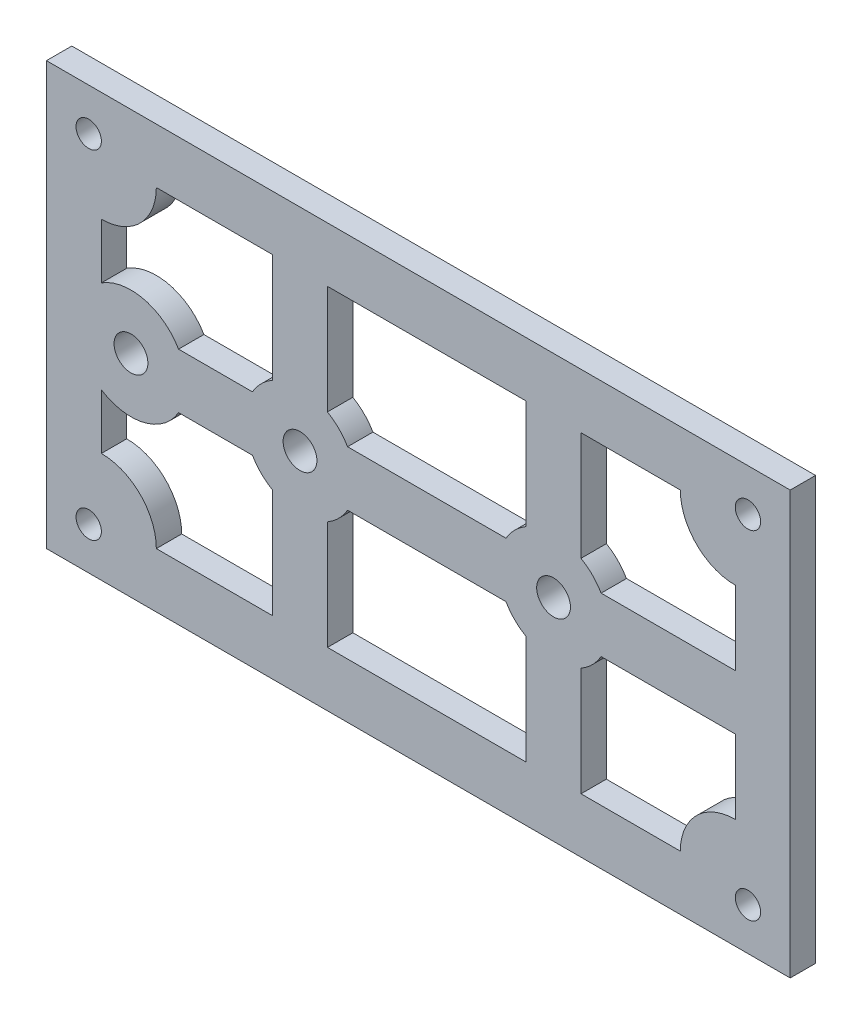
SolidWorks part; units mm, degrees
ref_plane "Front Plane" through (0, 0, 0) normal (0, 0, 1) x (1, 0, 0)
ref_plane "Top Plane" through (0, 0, 0) normal (0, 1, 0) x (1, 0, 0)
ref_plane "Right Plane" through (0, 0, 0) normal (1, 0, 0) x (0, 0, -1)
sketch "Sketch1" plane through (0, 0, 0) normal (0, 0, 1) x (1, 0, 0)
  line L0 (-44, 0) -> (44, 0) construction
  line L1 (-44, 25) -> (44, 25)
  line L2 (-44, 25) -> (-44, -25)
  line L3 (-44, -25) -> (44, -25)
  line L4 (44, 25) -> (44, -25)
  line L5 (0, 25) -> (0, -25) construction
  point P0 (0, 0)
  dimension "D1" = 50
  dimension "D2" = 88
extrude "Boss-Extrude1" add sketch "Sketch1" along normal blind 3
sketch "Sketch2" plane through (0, 0, 3) normal (0, 0, 1) x (1, 0, 0)
  line L0 (0, 0) -> (-110.6063, 0) construction
  line L1 (-44, 25) -> (-44, -25) construction
  circle A0 centre (-34, 0) radius 2
  circle A1 centre (-14, 0) radius 2
  circle A2 centre (16, 0) radius 2
  dimension "D1" = 4
  dimension "D4" = 30
  dimension "D2" = 20
  dimension "D3" = 10
extrude "Cut-Extrude1" cut sketch "Sketch2" against normal through all
sketch "Sketch3" plane through (0, 0, 3) normal (0, 0, 1) x (1, 0, 0)
  line L0 (-44, 25) -> (-44, -25) construction
  line L1 (44, 25) -> (-44, 25) construction
  circle A0 centre (-39, 20) radius 1.5
  dimension "D1" = 3
  dimension "D2" = 5
  dimension "D3" = 5
extrude "Cut-Extrude2" cut sketch "Sketch3" against normal through all
pattern_linear "LPattern1" count 2 spacing 78 along (1, 0, 0) count 2 spacing 40 along (0, -1, 0) of "Cut-Extrude2"
sketch "Sketch4" plane through (0, 0, 3) normal (0, 0, 1) x (1, 0, 0)
  line L0 (-14, 0) -> (-14, 31.6266) construction
  line L1 (16, 0) -> (16, 31.6266) construction
  line L14 (37.5, 3.25) -> (37.5, 12)
  line L15 (-28.3708, 3.25) -> (-19.6292, 3.25)
  line L16 (-8.3708, 3.25) -> (10.3708, 3.25)
  line L17 (-28.3708, -3.25) -> (-19.6292, -3.25)
  line L18 (37.5, -18.5) -> (37.5, 18.5)
  line L19 (-37.5, -18.5) -> (37.5, -18.5)
  line L20 (-37.5, 18.5) -> (-37.5, -18.5)
  line L21 (37.5, 18.5) -> (-37.5, 18.5)
  line L22 (37.5, -12) -> (37.5, -3.25)
  line L23 (-31, -18.5) -> (-17.25, -18.5)
  line L24 (-37.5, 12) -> (-37.5, 5.4772)
  line L25 (31, 18.5) -> (19.25, 18.5)
  line L26 (-8.3708, -3.25) -> (10.3708, -3.25)
  line L27 (21.6292, -3.25) -> (37.5, -3.25)
  line L28 (21.6292, 3.25) -> (37.5, 3.25)
  line L29 (-17.25, 18.5) -> (-31, 18.5)
  line L30 (12.75, 18.5) -> (-10.75, 18.5)
  line L31 (-17.25, 18.5) -> (-17.25, 5.6292)
  line L32 (19.25, -18.5) -> (31, -18.5)
  line L33 (-10.75, 18.5) -> (-10.75, 5.6292)
  line L34 (-17.25, -5.6292) -> (-17.25, -18.5)
  line L35 (19.25, -18.5) -> (19.25, -5.6292)
  line L36 (-10.75, -18.5) -> (12.75, -18.5)
  line L37 (12.75, -18.5) -> (12.75, -5.6292)
  line L38 (-10.75, -5.6292) -> (-10.75, -18.5)
  line L39 (12.75, 5.6292) -> (12.75, 18.5)
  line L40 (19.25, 5.6292) -> (19.25, 18.5)
  line L41 (-37.5, -5.4772) -> (-37.5, -12)
  line L42 (-34, 0) -> (16, 0) construction
  circle A70 centre (-34, 0) radius 2 construction
  arc A71 (-37.5, 12) -> (-31, 18.5) centre (-37.5, 18.5) ccw
  circle A73 centre (-14, 0) radius 2 construction
  arc A74 (31, 18.5) -> (37.5, 12) centre (37.5, 18.5) ccw
  circle A87 centre (16, 0) radius 2 construction
  arc A88 (-37.5, -5.4772) -> (-28.3708, -3.25) centre (-34, 0) ccw
  arc A91 (-19.6292, -3.25) -> (-17.25, -5.6292) centre (-14, 0) ccw
  arc A94 (10.3708, -3.25) -> (12.75, -5.6292) centre (16, 0) ccw
  arc A97 (-31, -18.5) -> (-37.5, -12) centre (-37.5, -18.5) ccw
  arc A98 (-28.3708, 3.25) -> (-37.5, 5.4772) centre (-34, 0) ccw
  arc A100 (37.5, -12) -> (31, -18.5) centre (37.5, -18.5) ccw
  arc A101 (-8.3708, 3.25) -> (-10.75, 5.6292) centre (-14, 0) ccw
  arc A102 (21.6292, 3.25) -> (19.25, 5.6292) centre (16, 0) ccw
  arc A103 (19.25, -5.6292) -> (21.6292, -3.25) centre (16, 0) ccw
  arc A104 (12.75, 5.6292) -> (10.3708, 3.25) centre (16, 0) ccw
  arc A105 (-10.75, -5.6292) -> (-8.3708, -3.25) centre (-14, 0) ccw
  arc A106 (-17.25, 5.6292) -> (-19.6292, 3.25) centre (-14, 0) ccw
  dimension "D1" = 6.5
  dimension "D2" = 6.5
  dimension "D3" = 6.5
  dimension "D4" = 6.5
  dimension "D8" = 6.5
extrude "Cut-Extrude3" cut sketch "Sketch4" against normal through all
equation "\"D3@LPattern1\" = \"D2@Sketch1\" - 10"
equation "\"D4@LPattern1\"= \"D1@Sketch1\" - 10"
